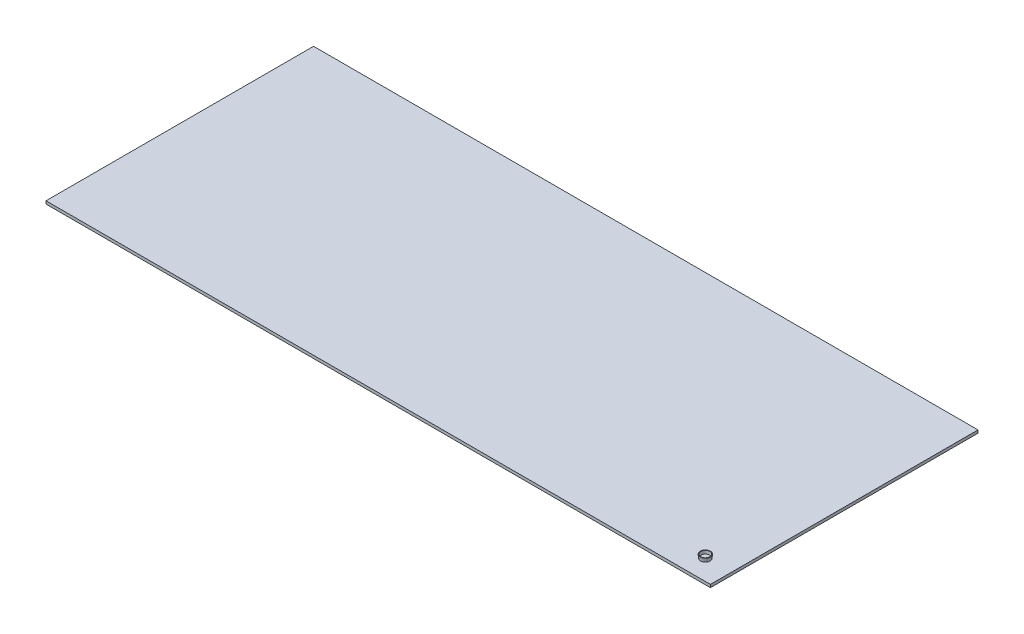
SolidWorks part; units mm, degrees
ref_plane "Front Plane" through (0, 0, 0) normal (0, 0, 1) x (1, 0, 0)
ref_plane "Top Plane" through (0, 0, 0) normal (0, 1, 0) x (1, 0, 0)
ref_plane "Right Plane" through (0, 0, 0) normal (1, 0, 0) x (0, 0, -1)
sketch "Sketch1" plane through (0, 0, 0) normal (0, 1, 0) x (1, 0, 0)
  line L0 (138.4999, -86.3785) -> (-138.4999, -86.3785)
  line L1 (138.4999, -86.3785) -> (138.4999, 25.1766)
  line L2 (138.4999, 25.1766) -> (-138.4999, 25.1766)
  line L3 (-138.4999, -86.3785) -> (-138.4999, 25.1766)
  line L4 (0, -61.3553) -> (0, 61.3553) construction
  point P4 (127.9999, -78.0035)
  point P5 (99.9999, -78.0035)
  point P6 (80.9999, -78.0035)
  point P7 (61.9999, -78.0035)
  point P8 (42.9999, -78.0035)
  point P9 (23.9999, -78.0035)
  point P10 (4.9999, -78.0035)
  point P11 (-14.0001, -78.0035)
  point P12 (-33.0001, -78.0035)
  point P13 (-52.0001, -78.0035)
  point P14 (-71.0001, -78.0035)
  point P15 (-90.0001, -78.0035)
  point P16 (-109.0001, -78.0035)
  point P17 (-128.0001, -78.0035)
  point P18 (-123.4999, -61.2535)
  point P19 (-100.0001, -61.2535)
  point P20 (-81.0001, -61.2535)
  point P21 (-62.0001, -61.2535)
  point P22 (-43.0001, -61.2535)
  point P23 (-24.0001, -61.2535)
  point P24 (-5.0001, -61.2535)
  point P25 (13.9999, -61.2535)
  point P26 (32.9999, -61.2535)
  point P27 (51.9999, -61.2535)
  point P28 (70.9999, -61.2535)
  point P29 (89.9999, -61.2535)
  point P30 (108.9999, -61.2535)
  point P31 (127.9999, -61.2535)
  point P32 (126.0001, -42.2535)
  point P33 (123.5001, -23.2535)
  point P34 (118.5001, -4.2535)
  point P35 (127.9999, 14.7465)
  point P36 (108.9999, 14.7465)
  point P37 (89.9999, 14.7465)
  point P38 (70.9999, 14.7465)
  point P39 (44.5001, 14.7465)
  point P40 (9.5001, 14.7465)
  point P41 (-25.4999, 14.7465)
  point P42 (-52.0001, 14.7465)
  point P43 (-71.0001, 14.7465)
  point P44 (-89.9999, 19.2278)
  point P45 (-108.9999, 19.2453)
  point P46 (-127.9999, 19.2453)
  point P47 (-108.9999, 10.2453)
  point P48 (-113.9999, -4.2535)
  point P49 (-123.3923, -20.6849)
  point P50 (-132.532, -20.6849)
  point P51 (-119.8923, -44.7983)
  point P52 (-131.032, -44.8246)
  point P53 (-109.0001, -23.2535)
  point P54 (-104.0001, -42.2535)
  point P55 (-85.0001, -42.2535)
  point P56 (-90.0001, -23.2535)
  point P57 (-81.0001, -4.2535)
  point P58 (-62.0001, -4.2535)
  point P59 (-71.0001, -23.2535)
  point P60 (-66.0001, -42.2535)
  point P61 (-47.0001, -42.2535)
  point P62 (-52.0001, -23.2535)
  point P63 (-43.0001, -4.2535)
  point P64 (-33.0001, -23.2535)
  point P65 (-28.0001, -42.2535)
  point P66 (-24.0001, -4.2535)
  point P67 (-14.0001, -23.2535)
  point P68 (-9.0001, -42.2535)
  point P69 (-5.0001, -4.2535)
  point P70 (4.9999, -23.2535)
  point P71 (9.9999, -42.2535)
  point P72 (28.9999, -42.2535)
  point P73 (23.9999, -23.2535)
  point P74 (13.9999, -4.2535)
  point P75 (32.9999, -4.2535)
  point P76 (51.9999, -4.2535)
  point P77 (42.9999, -23.2535)
  point P78 (61.9999, -23.2535)
  point P79 (47.9999, -42.2535)
  point P80 (66.9999, -42.2535)
  point P81 (80.9999, -23.2535)
  point P82 (70.9999, -4.2535)
  point P83 (89.9999, -4.2535)
  point P84 (85.9999, -42.2535)
  point P85 (99.9999, -23.2535)
  point P86 (104.9999, -42.2535)
  point P87 (0, 0)
  point P88 (0, 0)
  point P89 (0, 0)
  point P90 (0, 0)
  point P91 (0, 0)
  point P92 (0, 0)
  dimension "D1" = 10.5
  dimension "D2" = 8.375
  dimension "D3" = 28
  dimension "D4" = 19
  dimension "D5" = 19
  dimension "D6" = 19
  dimension "D7" = 19
  dimension "D8" = 19
  dimension "D9" = 19
  dimension "D10" = 19
  dimension "D11" = 19
  dimension "D12" = 19
  dimension "D13" = 19
  dimension "D14" = 19
  dimension "D15" = 19
  dimension "D16" = 10.5
  dimension "D17" = 12.4998
  dimension "D18" = 14.9998
  dimension "D19" = 19.9998
  dimension "D20" = 10.5
  dimension "D21" = 19
  dimension "D22" = 19
  dimension "D23" = 19
  dimension "D24" = 19
  dimension "D25" = 19
  dimension "D26" = 19
  dimension "D27" = 19
  dimension "D28" = 19
  dimension "D29" = 19
  dimension "D30" = 19
  dimension "D31" = 19
  dimension "D32" = 19
  dimension "D33" = 23.4998
  dimension "D34" = 21.0002
  dimension "D35" = 23.5002
  dimension "D36" = 28.5002
  dimension "D37" = 19
  dimension "D38" = 19
  dimension "D39" = 19
  dimension "D40" = 19
  dimension "D41" = 19
  dimension "D42" = 19
  dimension "D43" = 19
  dimension "D44" = 19
  dimension "D45" = 19
  dimension "D46" = 19
  dimension "D47" = 19
  dimension "D48" = 19
  dimension "D49" = 19
  dimension "D50" = 15.8922
  dimension "D51" = 11.1396
  dimension "D52" = 9.1396
  dimension "D53" = 14.3922
  dimension "D54" = 19
  dimension "D55" = 19
  dimension "D56" = 19
  dimension "D57" = 19
  dimension "D58" = 19
  dimension "D59" = 19
  dimension "D60" = 19
  dimension "D61" = 19
  dimension "D62" = 19
  dimension "D63" = 19
  dimension "D64" = 19
  dimension "D65" = 19
  dimension "D66" = 19
  dimension "D67" = 19
  dimension "D68" = 19
  dimension "D69" = 19
  dimension "D70" = 19
  dimension "D71" = 19
  dimension "D72" = 19
  dimension "D73" = 32.9998
  dimension "D74" = 19
  dimension "D75" = 19
  dimension "D76" = 9
  dimension "D77" = 5.9314
  dimension "D78" = 19
  dimension "D79" = 18.9998
  dimension "D80" = 19
  dimension "D81" = 26.5002
  dimension "D82" = 35
  dimension "D83" = 35
  dimension "D84" = 26.4998
  dimension "D85" = 19
  dimension "D86" = 19
  dimension "D87" = 10.4302
  dimension "D88" = 138.4999
extrude "Boss-Extrude1" add sketch "Sketch1" along normal mid plane 1.2
ref_axis "Axis1" through (127.9999, -51.5328, 78.0035) along (0, 1, 0)
ref_plane "Plane1" through (0, 0, 78.0035) normal (0, 0, -1) x (-1, 0, 0)
sketch "Sketch2" plane through (0, 0, 78.0035) normal (0, 0, -1) x (-1, 0, 0)
  line L0 (-127.9999, 0.6) -> (-125.9999, 0.6)
  line L1 (-138.4999, 0.6) -> (138.4999, 0.6) construction
  line L2 (-127.9999, -51.5328) -> (-127.9999, 47.0116) construction
  line L11 (-127.9999, 0.85) -> (-127.9999, 0.6)
  line L12 (-125.9999, 0.6) -> (-125.8687, 2.1)
  line L13 (-125.8687, 2.1) -> (-126.1187, 2.1)
  line L14 (-126.1187, 2.1) -> (-126.228, 0.85)
  line L15 (-126.228, 0.85) -> (-127.9999, 0.85)
  dimension "D1" = 0.25
  dimension "D2" = 2
  dimension "D3" = 85
  dimension "D4" = 1.5
  dimension "D5" = 0.25
revolve "Revolve1" add sketch "Sketch2" angle 360 about axis through (127.9999, -51.5328, 78.0035) along (0, 1, 0)
sketch "Sketch4" plane through (0, 0, 78.0035) normal (0, 0, -1) x (-1, 0, 0)
  line L1 (-129.9999, 0.6) -> (-129.8949, -0.6) construction
  line L2 (-138.4999, -0.6) -> (138.4999, -0.6) construction
  line L4 (-129.8949, -0.6) -> (-129.9999, 0.6)
  line L5 (-129.9999, 0.6) -> (-127.9999, 0.6)
  line L6 (-127.9999, -51.5328) -> (-127.9999, 47.0116) construction
  line L7 (-138.4999, 0.6) -> (138.4999, 0.6) construction
  line L8 (-127.9999, 0.6) -> (-127.9999, -0.6)
  line L9 (-127.9999, -0.6) -> (-129.8949, -0.6)
revolve "Cut-Revolve1" cut sketch "Sketch4" angle 360 about axis through (127.9999, -51.5328, 78.0035) along (0, 1, 0)
